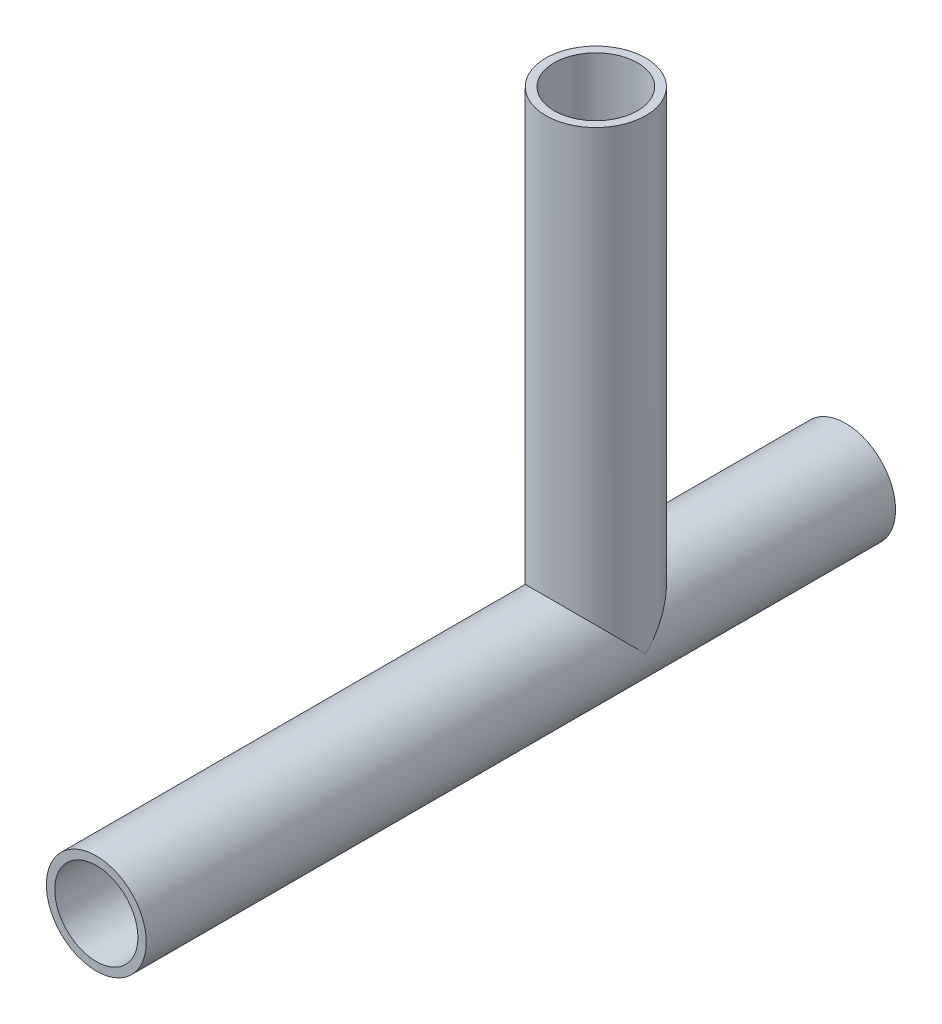
SolidWorks part; units mm, degrees
ref_plane "Plan de face" through (0, 0, 0) normal (0, 0, 1) x (1, 0, 0)
ref_plane "Plan de dessus" through (0, 0, 0) normal (0, 1, 0) x (1, 0, 0)
ref_plane "Plan de droite" through (0, 0, 0) normal (1, 0, 0) x (0, 0, -1)
sketch "Esquisse1" plane through (0, 0, 0) normal (0, 0, 1) x (1, 0, 0)
  circle A0 centre (0, 0) radius 3
  circle A1 centre (0, 0) radius 2.5
  dimension "D1" = 6
  dimension "D2" = 5
extrude "Boss.-Extru.1" add sketch "Esquisse1" along normal blind 30 and the other way blind 15
sketch "Esquisse2" plane through (0, 0, 0) normal (0, 1, 0) x (1, 0, 0)
  circle A0 centre (0, 0) radius 3
  circle A1 centre (0, 0) radius 2.5
  dimension "D1" = 6
  dimension "D2" = 5
extrude "Boss.-Extru.2" add sketch "Esquisse2" along normal blind 28
